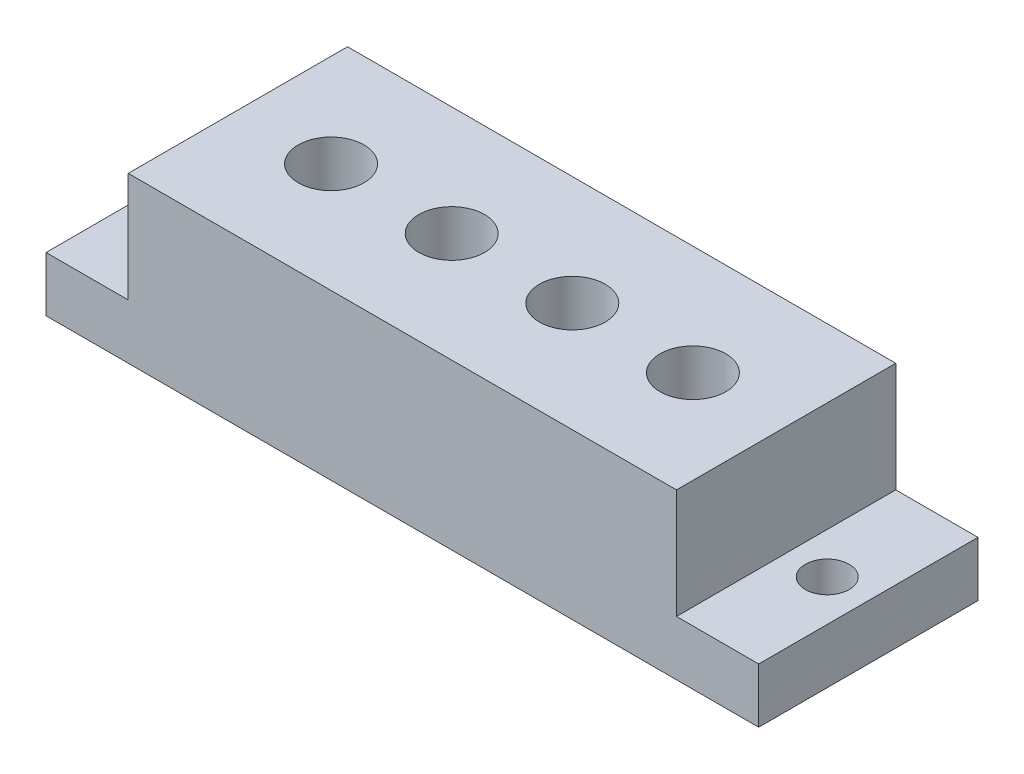
SolidWorks part; units mm, degrees
ref_plane "前视基准面" through (0, 0, 0) normal (0, 0, 1) x (1, 0, 0)
ref_plane "上视基准面" through (0, 0, 0) normal (0, 1, 0) x (1, 0, 0)
ref_plane "右视基准面" through (0, 0, 0) normal (1, 0, 0) x (0, 0, -1)
sketch "草图1" plane through (0, 0, 0) normal (0, 1, 0) x (1, 0, 0)
  line L0 (-65, 20) -> (65, 20)
  line L1 (65, 20) -> (65, -20)
  line L2 (65, -20) -> (-65, -20)
  line L3 (-65, -20) -> (-65, 20)
extrude "凸台-拉伸1" add sketch "草图1" along normal blind 10
ref_plane "基准面1" through (0, 10, 0) normal (0, 1, 0) x (1, 0, 0)
sketch "草图2" plane through (0, 10, 0) normal (0, 1, 0) x (1, 0, 0)
  line L0 (-50, 20) -> (50, 20)
  line L1 (50, 20) -> (50, -20)
  line L2 (50, -20) -> (-50, -20)
  line L3 (-50, -20) -> (-50, 20)
extrude "凸台-拉伸2" add sketch "草图2" along normal blind 20
ref_plane "基准面2" through (0, 30, 0) normal (0, 1, 0) x (1, 0, 0)
sketch "草图3" plane through (0, 30, 0) normal (0, 1, 0) x (1, 0, 0)
  circle A0 centre (-33, 0) radius 6
  circle A1 centre (-11, 0) radius 6
  circle A2 centre (11, 0) radius 6
  circle A3 centre (33, 0) radius 6
extrude "切除-拉伸1" cut sketch "草图3" against normal blind 20
sketch "草图4" plane through (0, 30, 0) normal (0, 1, 0) x (1, 0, 0)
  circle A0 centre (-57.5, 0) radius 4
  circle A1 centre (57.5, 0) radius 4
extrude "切除-拉伸2" cut sketch "草图4" against normal through all
